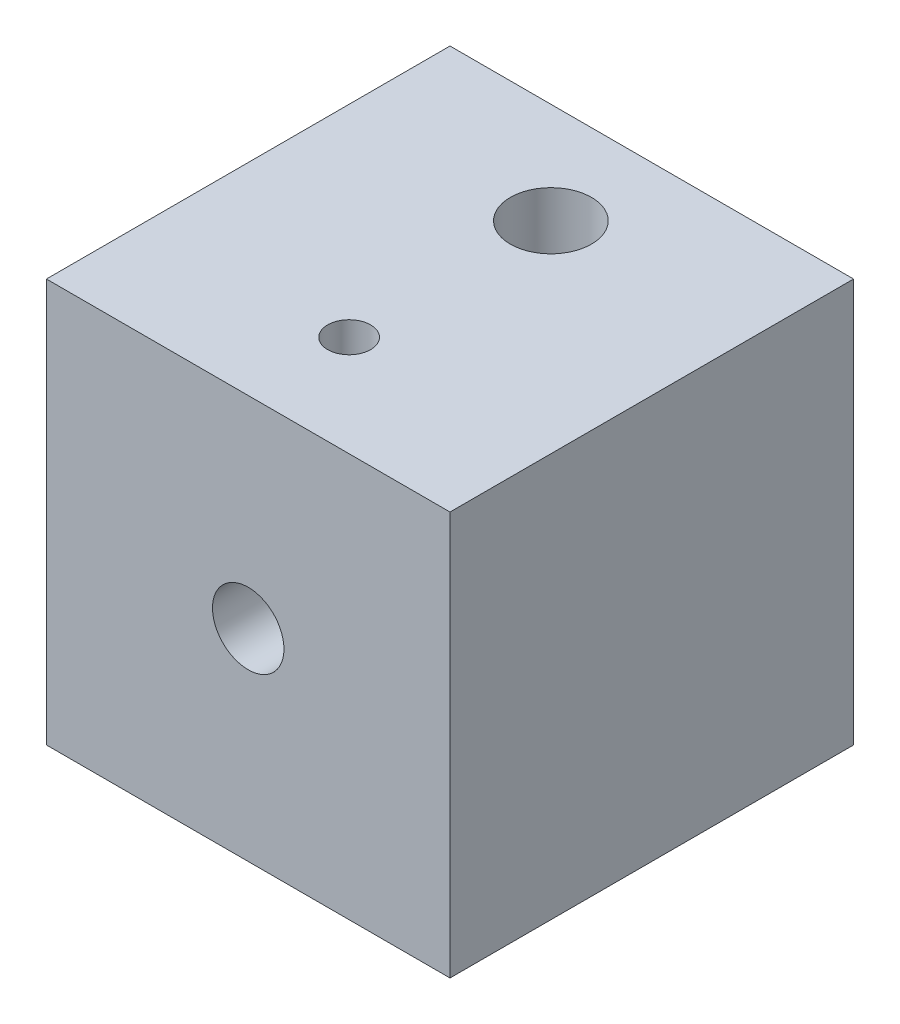
SolidWorks part; units mm, degrees
ref_plane "Front" through (0, 0, 0) normal (0, 0, 1) x (1, 0, 0)
ref_plane "Top" through (0, 0, 0) normal (0, 1, 0) x (1, 0, 0)
ref_plane "Right" through (0, 0, 0) normal (1, 0, 0) x (0, 0, -1)
sketch "Sketch1" plane through (0, 0, 0) normal (0, 1, 0) x (1, 0, 0)
  line L1 (12.7, -12.7) -> (-12.7, -12.7)
  line L2 (12.7, -12.7) -> (12.7, 12.7)
  line L3 (12.7, 12.7) -> (-12.7, 12.7)
  line L4 (-12.7, -12.7) -> (-12.7, 12.7)
  line L5 (12.7, -12.7) -> (-12.7, 12.7) construction
  line L6 (12.7, 12.7) -> (-12.7, -12.7) construction
  point P0 (0, 0)
  dimension "D1" = 25.4
  dimension "D2" = 25.4
extrude "Boss-Extrude1" add sketch "Sketch1" along normal blind 25.4
sketch "Sketch2" plane through (0, 0, 12.7) normal (0, 0, 1) x (1, 0, 0)
  line L0 (0, 25.4) -> (0, 0) construction
  line L1 (-12.7, 25.4) -> (12.7, 25.4) construction
  circle A0 centre (0, 12.7) radius 2.25
  dimension "D1" = 4.5
extrude "Cut-Extrude1" cut sketch "Sketch2" against normal blind 12.7
sketch "Sketch3" plane through (0, 0, -12.7) normal (0, 0, -1) x (-1, 0, 0)
  line L0 (0, 25.4) -> (0, 0) construction
  line L1 (-12.7, 25.4) -> (12.7, 25.4) construction
  circle A0 centre (0, 12.7) radius 6.985
  dimension "D1" = 13.97
extrude "Cut-Extrude2" cut sketch "Sketch3" against normal blind 12.7
hole_wizard "#6-32 Tapped Hole1" positions "Sketch6" profile "Sketch7" tap size "#6-32" standard "ANSI Inch"
sketch "Sketch6" plane through (0, 25.4, 0) normal (0, 1, 0) x (1, 0, 0)
  line L0 (12.7, 0) -> (-12.7, 0) construction
  line L1 (-12.7, 12.7) -> (-12.7, -12.7) construction
  line L3 (0, 0) -> (0, -12.7) construction
  line L4 (-12.7, -12.7) -> (12.7, -12.7) construction
  point P39 (0, -6.35)
sketch "Sketch7" plane through (0, 25.4, 6.35) normal (1, 0, 0) x (0, 0, 1)
  line L0 (0, 0) -> (0, 10.45)
  line L1 (0, 10.45) -> (1.3525, 10.45)
  line L2 (1.3525, 10.45) -> (1.3525, 0)
  line L5 (1.3525, 0) -> (0, 0)
  line L11 (0, -6.35) -> (0, 107.95) construction
  dimension "Thru Tap Drill Dia." = 2.7051
  dimension "Thru Tap Drill Depth" = 10.45
cosmetic thread "Hole Thread1" parameters "D2"=3.5052
hole_wizard "1/4-20 Tapped Hole2" positions "Sketch8" profile "Sketch9" tap size "1/4-20" standard "ANSI Inch"
sketch "Sketch8" plane through (0, 25.4, 0) normal (0, 1, 0) x (1, 0, 0)
  line L0 (-12.7, 0) -> (12.7, 0) construction
  line L1 (-12.7, 12.7) -> (-12.7, -12.7) construction
  line L2 (12.7, -12.7) -> (12.7, 12.7) construction
  line L3 (0, 0) -> (0, 12.7) construction
  line L4 (12.7, 12.7) -> (-12.7, 12.7) construction
  point P16 (0, 6.35)
sketch "Sketch9" plane through (0, 25.4, -6.35) normal (1, 0, 0) x (0, 0, 1)
  line L0 (0, 0) -> (0, 5.715)
  line L1 (0, 5.715) -> (2.5527, 5.715)
  line L2 (2.5527, 5.715) -> (2.5527, 0)
  line L5 (2.5527, 0) -> (0, 0)
  line L11 (0, -6.35) -> (0, 107.95) construction
  dimension "Thru Tap Drill Dia." = 5.1054
  dimension "Thru Tap Drill Depth" = 5.715
cosmetic thread "Hole Thread2" parameters "D2"=6.35
